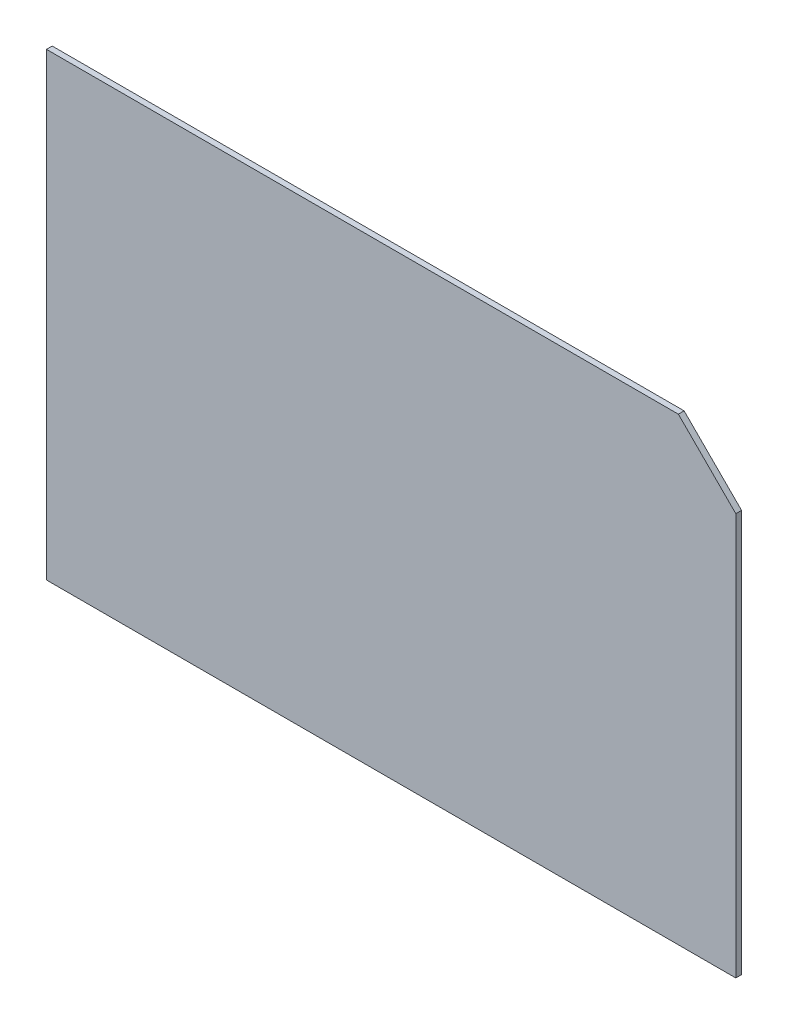
SolidWorks part; units mm, degrees
ref_plane "Front Plane" through (0, 0, 0) normal (0, 0, 1) x (1, 0, 0)
ref_plane "Top Plane" through (0, 0, 0) normal (0, 1, 0) x (1, 0, 0)
ref_plane "Right Plane" through (0, 0, 0) normal (1, 0, 0) x (0, 0, -1)
sketch "Sketch2" plane through (0, 0, 0) normal (0, 0, 1) x (1, 0, 0)
  line L1 (-1500, 1000) -> (1500, 1000)
  line L2 (-1500, 1000) -> (-1500, -1000)
  line L3 (-1500, -1000) -> (1500, -1000)
  line L4 (1500, 1000) -> (1500, -1000)
  dimension "wall_length" = 3000
  dimension "wall_height" = 2000
  dimension "D1" = 1500
  dimension "D2" = 1000
extrude "Boss-Extrude1" add sketch "Sketch2" against normal blind 25
sketch "Sketch3" plane through (0, 0, 0) normal (0, 0, 1) x (1, 0, 0)
  line L5 (1500, 750) -> (1500, 1000)
  line L6 (1500, -1000) -> (1500, 1000) construction
  line L7 (1500, 1000) -> (1250, 1000)
  line L8 (1500, 1000) -> (-1500, 1000) construction
  line L9 (1250, 1000) -> (1500, 750)
  dimension "D1" = 250
  dimension "D2" = 45
extrude "Cut-Extrude1" cut sketch "Sketch3" against normal blind 932
equation "\"D1@Sketch2\"=\"wall_length@Sketch2\"/2"
equation "\"D2@Sketch2\"=\"wall_height@Sketch2\"/2"
